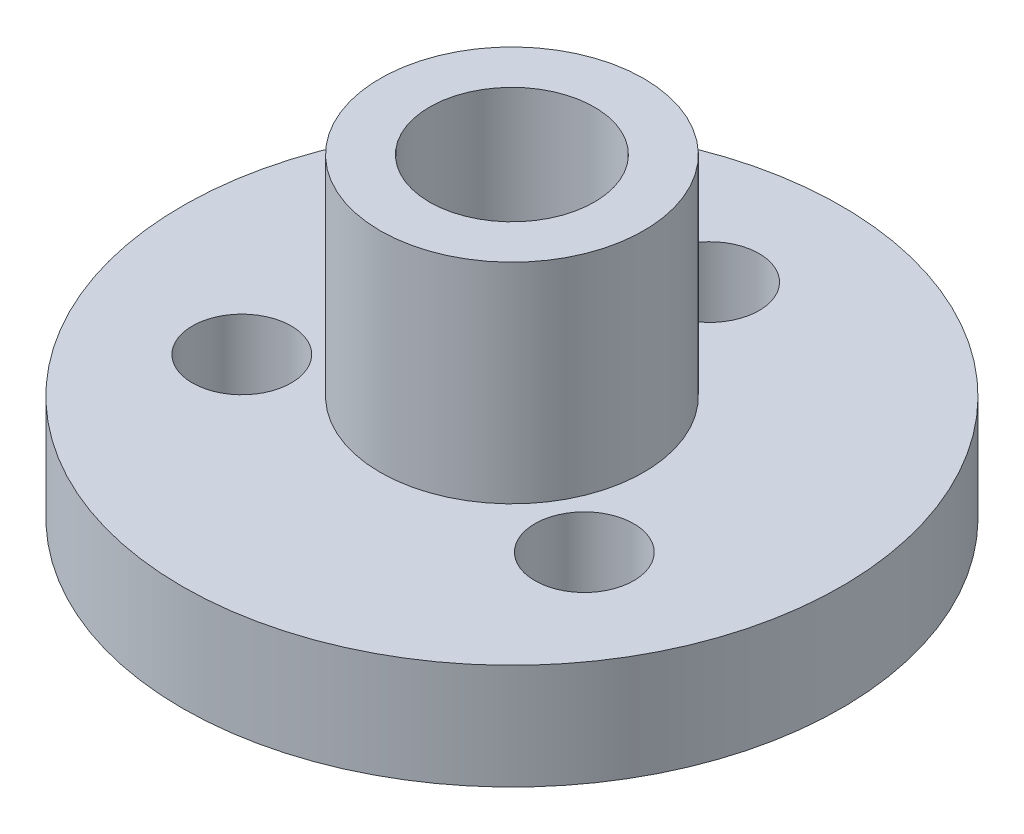
SolidWorks part; units mm, degrees
ref_plane "Front Plane" through (0, 0, 0) normal (0, 0, 1) x (1, 0, 0)
ref_plane "Top Plane" through (0, 0, 0) normal (0, 1, 0) x (1, 0, 0)
ref_plane "Right Plane" through (0, 0, 0) normal (1, 0, 0) x (0, 0, -1)
sketch "Sketch1" plane through (0, 0, 0) normal (0, 0, 1) x (1, 0, 0)
  line L0 (0, 12.5098) -> (0, -10.969) construction
  line L1 (-19.48, 0) -> (19.0398, 0) construction
  line L2 (-2.5, 9.55) -> (-2.5, 0)
  line L3 (-2.5, 0) -> (-10, 0)
  line L4 (-10, 0) -> (-10, 3.2)
  line L5 (-10, 3.2) -> (-4, 3.2)
  line L6 (-4, 3.2) -> (-4, 9.55)
  line L7 (-4, 9.55) -> (-2.5, 9.55)
  dimension "D1" = 4
  dimension "D2" = 9.55
  dimension "D3" = 10
  dimension "D4" = 3.2
  dimension "D5" = 1.5
revolve "Revolve1" add sketch "Sketch1" angle 360 about L0
sketch "Sketch2" plane through (0, 3.2, 0) normal (0, 1, 0) x (1, 0, 0)
  line L0 (0, 0) -> (0, 10) construction
  circle A0 centre (0, 0) radius 6 construction
  circle A1 centre (0, 0) radius 10 construction
  circle A2 centre (0, 6) radius 1.5
  circle A3 centre (5.1962, -3) radius 1.5
  circle A4 centre (-5.1962, -3) radius 1.5
  point P15 (0, 0)
  dimension "D1" = 12
  dimension "D2" = 3
  dimension "D4" = 10.3923
  dimension "D3" = 3
extrude "Cut-Extrude1" cut sketch "Sketch2" against normal through all
